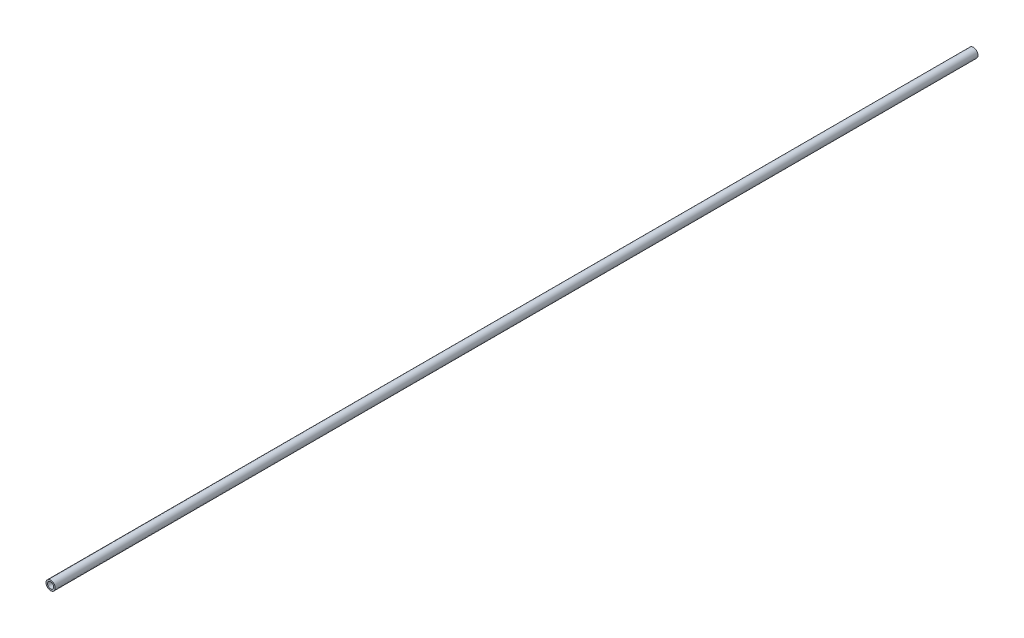
SolidWorks part; units mm, degrees
material "Tubi carbonio"
ref_plane "Piano frontale" through (0, 0, 0) normal (0, 0, 1) x (1, 0, 0)
ref_plane "Piano superiore" through (0, 0, 0) normal (0, 1, 0) x (1, 0, 0)
ref_plane "Piano destro" through (0, 0, 0) normal (1, 0, 0) x (0, 0, -1)
sketch "Schizzo1" plane through (0, 0, 0) normal (0, 0, 1) x (1, 0, 0)
  circle A0 centre (0, 0) radius 3
  circle A1 centre (0, 0) radius 2
  dimension "D1" = 4
  dimension "D2" = 6
extrude "Estrusione-Estrusione1" add sketch "Schizzo1" along normal blind 600
